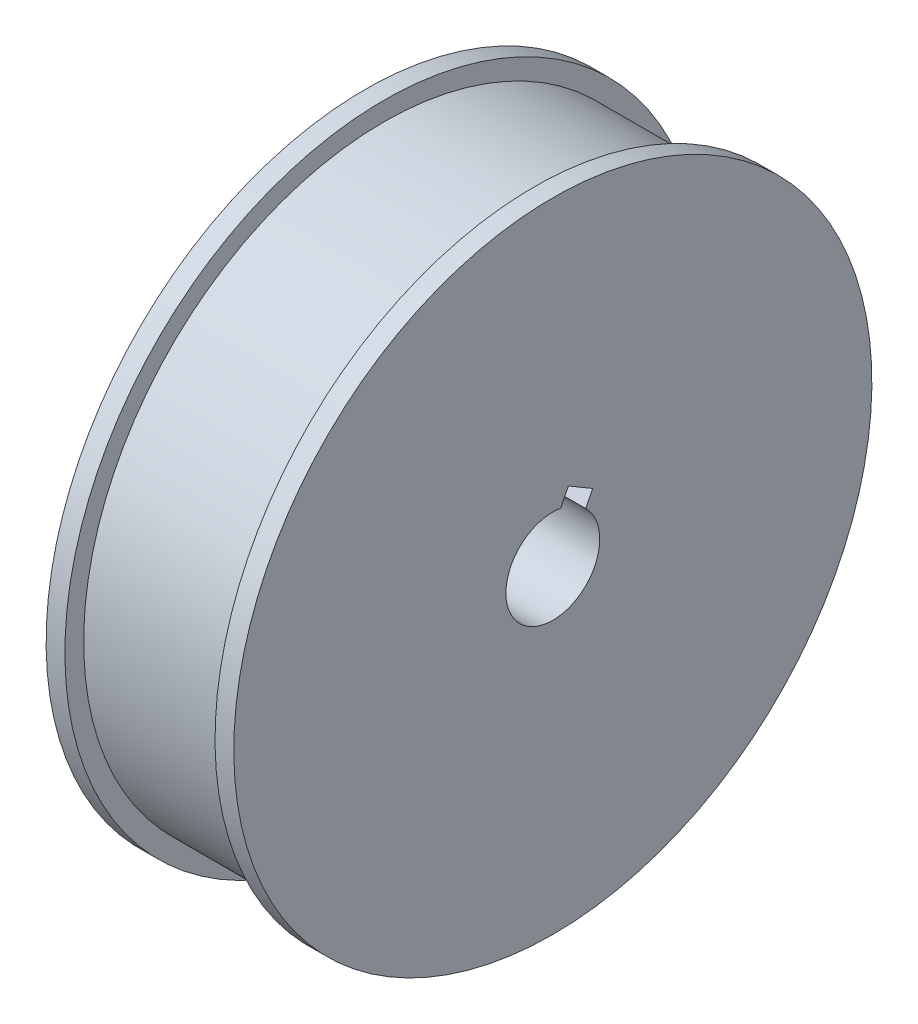
SolidWorks part; units mm, degrees
ref_plane "Front Plane" through (0, 0, 0) normal (0, 0, 1) x (1, 0, 0)
ref_plane "Top Plane" through (0, 0, 0) normal (0, 1, 0) x (1, 0, 0)
ref_plane "Right Plane" through (0, 0, 0) normal (1, 0, 0) x (0, 0, -1)
sketch "Sketch1" plane through (0, 0, 0) normal (0, 0, 1) x (1, 0, 0)
  line L1 (-15.875, 0) -> (15.875, 0)
  line L2 (-15.875, 0) -> (-15.875, 50.8)
  line L3 (-15.875, 50.8) -> (15.875, 50.8)
  line L4 (15.875, 0) -> (15.875, 50.8)
  line L5 (-15.875, 50.8) -> (-12.7, 50.8)
  line L6 (-15.875, 50.8) -> (-15.875, 53.975)
  line L7 (-15.875, 53.975) -> (-12.7, 53.975)
  line L8 (-12.7, 50.8) -> (-12.7, 53.975)
  line L9 (15.875, 50.8) -> (12.7, 50.8)
  line L10 (15.875, 50.8) -> (15.875, 53.975)
  line L11 (15.875, 53.975) -> (12.7, 53.975)
  line L12 (12.7, 50.8) -> (12.7, 53.975)
  point P5 (0, 0)
  dimension "D1" = 50.8
  dimension "D2" = 31.75
  dimension "D3" = 3.175
  dimension "D4" = 3.175
revolve "Revolve1" add sketch "Sketch1" angle 360 about L1
sketch "Sketch2" plane through (-15.875, 0, 0) normal (-1, 0, 0) x (0, 0, 1)
  line L12 (-6.7456, 8.004) -> (-5.5567, 5.6681) construction
  line L13 (-2.6326, 10.4224) -> (-6.7456, 8.004) construction
  line L14 (-1.3123, 7.8283) -> (-2.6326, 10.4224) construction
  line L15 (-6.7456, 8.004) -> (-5.5567, 5.6681)
  line L16 (-2.6326, 10.4224) -> (-6.7456, 8.004)
  line L17 (-1.3123, 7.8283) -> (-2.6326, 10.4224)
  arc A4 (-5.5567, 5.6681) -> (-1.3123, 7.8283) centre (0, 0) ccw construction
  arc A5 (-5.5567, 5.6681) -> (-1.3123, 7.8283) centre (0, 0) ccw
extrude "Cut-Extrude1" cut sketch "Sketch2" against normal through all
